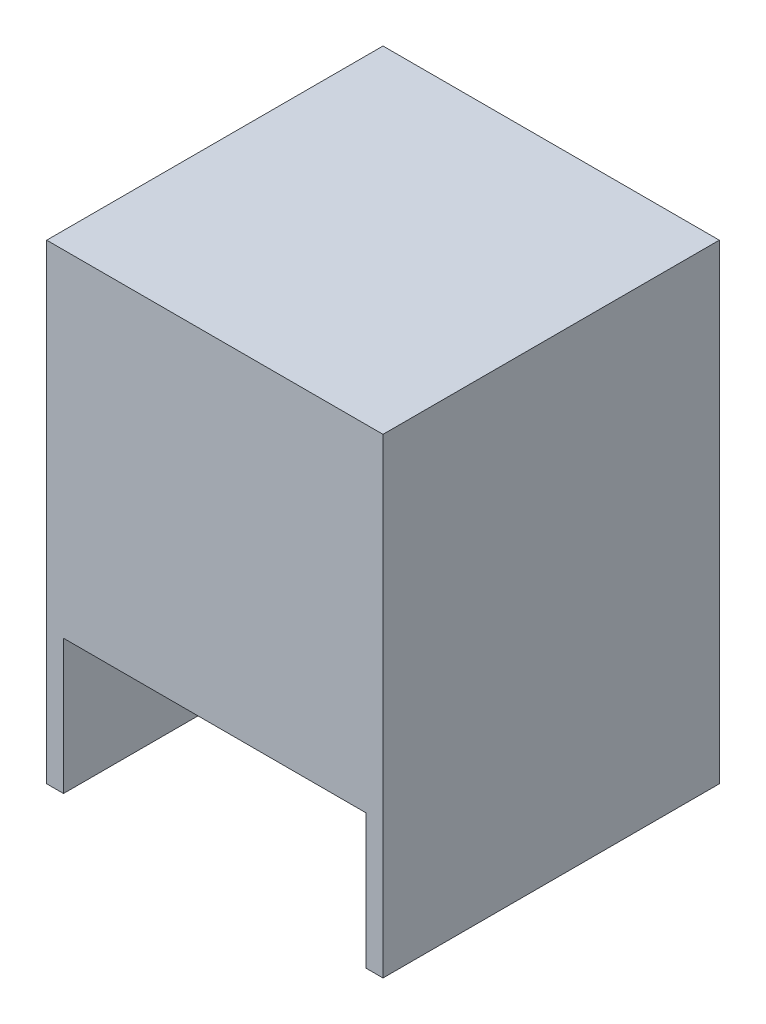
SolidWorks part; units mm, degrees
ref_plane "Front Plane" through (0, 0, 0) normal (0, 0, 1) x (1, 0, 0)
ref_plane "Top Plane" through (0, 0, 0) normal (0, 1, 0) x (1, 0, 0)
ref_plane "Right Plane" through (0, 0, 0) normal (1, 0, 0) x (0, 0, -1)
sketch "Sketch1" plane through (0, 0, 0) normal (0, 1, 0) x (1, 0, 0)
  line L1 (-500, 500) -> (500, 500)
  line L2 (-500, 500) -> (-500, -500)
  line L3 (-500, -500) -> (500, -500)
  line L4 (500, 500) -> (500, -500)
  line L5 (-500, 500) -> (500, -500) construction
  line L6 (-500, -500) -> (500, 500) construction
  point P0 (0, 0)
  dimension "D1" = 1000
  dimension "D2" = 1000
extrude "Boss-Extrude1" add sketch "Sketch1" along normal blind 1000
sketch "Sketch2" plane through (0, 0, 0) normal (0, -1, 0) x (1, 0, 0)
  line L0 (500, -500) -> (-500, -500) construction
  line L1 (-500, 500) -> (-450, 500)
  line L2 (-500, 500) -> (-500, -500)
  line L3 (-500, -500) -> (-450, -500)
  line L4 (-450, 500) -> (-450, -500)
  line L6 (500, 500) -> (450, 500)
  line L7 (500, 500) -> (500, -500)
  line L8 (500, -500) -> (450, -500)
  line L9 (450, 500) -> (450, -500)
  dimension "D1" = 50
  dimension "D2" = 50
extrude "Boss-Extrude2" add sketch "Sketch2" along normal blind 400
